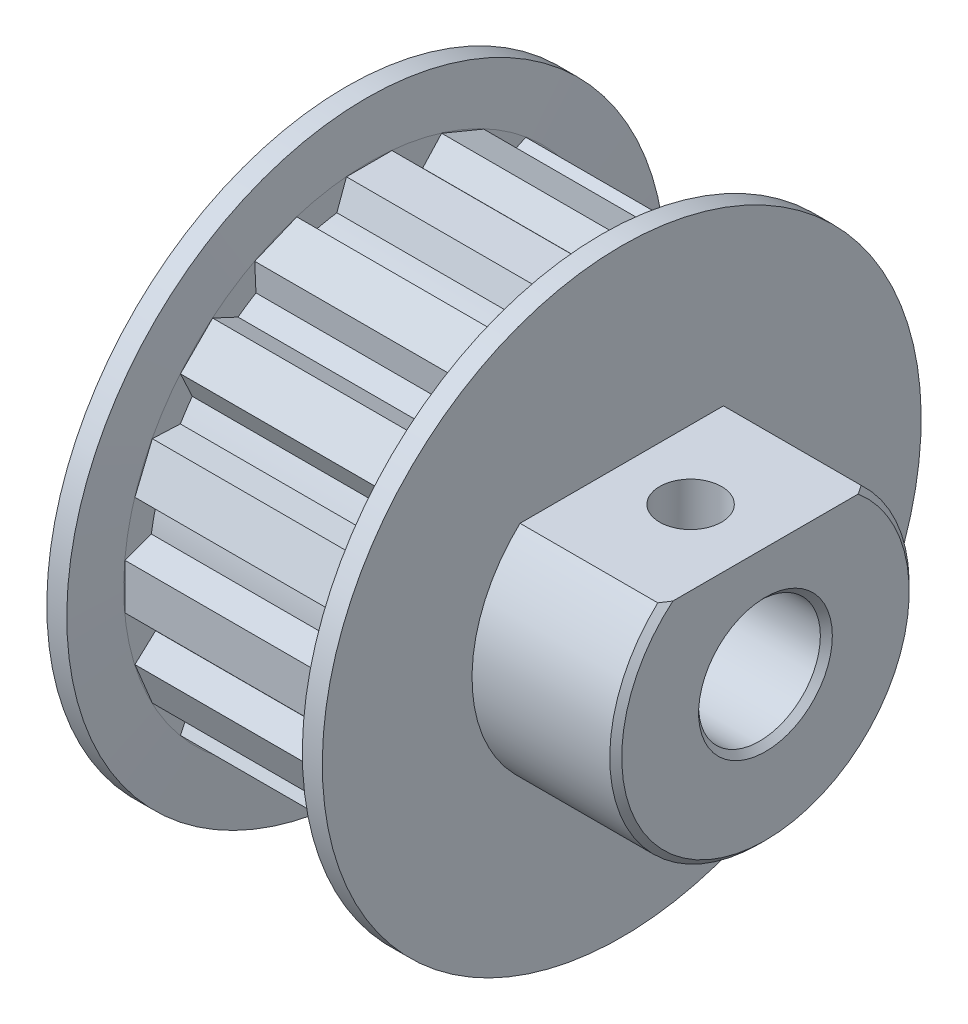
SolidWorks part; units mm, degrees
ref_plane "Front Plane" through (0, 0, 0) normal (0, 0, 1) x (1, 0, 0)
ref_plane "Top Plane" through (0, 0, 0) normal (0, 1, 0) x (1, 0, 0)
ref_plane "Right Plane" through (0, 0, 0) normal (1, 0, 0) x (0, 0, -1)
sketch "Sketch1" plane through (0, 0, 0) normal (0, 0, 1) x (1, 0, 0)
  line L0 (0, 15) -> (0, 0)
  line L1 (0, 0) -> (13.8, 0)
  line L2 (13.8, 0) -> (13.8, 15)
  line L3 (13.8, 15) -> (12.8, 15)
  line L4 (12.8, 15) -> (12.65, 12.3)
  line L5 (12.65, 12.3) -> (12.65, 11.0324)
  line L6 (12.65, 11.0324) -> (1.15, 11.0324)
  line L7 (1.15, 11.0324) -> (1.15, 12.3)
  line L8 (1.15, 12.3) -> (1, 15)
  line L9 (1, 15) -> (0, 15)
  line L10 (0, 0) -> (13.8, 0) construction
  dimension "D1" = 11.5
  dimension "D2" = 13.8
  dimension "D3" = 1.15
revolve "Revolve1" add sketch "Sketch1" angle 360 about L10
sketch "Sketch2" plane through (13.8, 0, 0) normal (1, 0, 0) x (0, 0, -1)
  circle A0 centre (0, 0) radius 7.5
extrude "Boss-Extrude1" add sketch "Sketch2" along normal blind 7.2
hole_wizard "Ø6.0 (6) Diameter Hole1" positions "Sketch4" profile "Sketch3" hole size "Ø6.0" standard "ANSI Metric"
sketch "Sketch4" plane through (21, 0, 0) normal (1, 0, 0) x (0, 0, -1)
  point P0 (0, 0)
sketch "Sketch3" plane through (21, 0, 0) normal (0, 1, 0) x (0, 0, -1)
  line L0 (0, 0) -> (0, 21)
  line L1 (0, 21) -> (3.05, 21)
  line L2 (3.05, 21) -> (3.05, 0)
  line L5 (3.05, 0) -> (0, 0)
  line L11 (0, -6.35) -> (0, 107.95) construction
  dimension "Thru Hole Dia." = 6.1
  dimension "Thru Hole Depth" = 21
ref_plane "Plane1" through (0, 0, 0) normal (0, -1, 0) x (1, 0, 0)
sketch "Sketch5" plane through (0, 0, 0) normal (0, -1, 0) x (1, 0, 0)
  line L0 (12.65, 12.2324) -> (1.15, 12.2324)
rib "Rib1" sketch "Sketch5" sketch "Sketch5" thickness 2.2803 extrusion direction parallel to sketch draft on yes draft angle 20 parameters "D1"=2.2803, "D3"=20
ref_plane "Plane2" through (0, 0, 0) normal (0, 0, -1) x (-1, 0, 0)
sketch "Sketch6" plane through (0, 0, 0) normal (0, 0, -1) x (-1, 0, 0)
  line L0 (-12.65, -12.2324) -> (-1.15, -12.2324)
rib "Rib2" sketch "Sketch6" sketch "Sketch6" thickness 2.2803 extrusion direction parallel to sketch draft on yes draft angle 20 parameters "D1"=2.2803, "D3"=20
sketch "Sketch7" plane through (0, 0, 0) normal (0, 1, 0) x (1, 0, 0)
  line L0 (12.65, 12.2324) -> (1.15, 12.2324)
rib "Rib3" sketch "Sketch7" sketch "Sketch7" thickness 2.2803 extrusion direction parallel to sketch draft on yes draft angle 20 parameters "D1"=2.2803, "D3"=20
sketch "Sketch8" plane through (0, 0, 0) normal (0, 0, 1) x (1, 0, 0)
  line L0 (12.65, 12.2324) -> (1.15, 12.2324)
rib "Rib4" sketch "Sketch8" sketch "Sketch8" thickness 2.2803 extrusion direction parallel to sketch draft on yes draft angle 20 parameters "D1"=2.2803, "D3"=20
ref_plane "Plane3" through (0, 0, 0) normal (0, -0.9239, -0.3827) x (1, 0, 0)
sketch "Sketch9" plane through (0, 0, 0) normal (0, -0.9239, -0.3827) x (1, 0, 0)
  line L0 (12.65, 12.2324) -> (1.15, 12.2324)
rib "Rib5" sketch "Sketch9" sketch "Sketch9" thickness 2.2803 extrusion direction parallel to sketch draft on yes draft angle 20 parameters "D1"=2.2803, "D3"=20
ref_plane "Plane4" through (0, 0, 0) normal (0, 0.9239, -0.3827) x (-1, 0, 0)
sketch "Sketch10" plane through (0, 0, 0) normal (0, 0.9239, -0.3827) x (-1, 0, 0)
  line L0 (-12.65, -12.2324) -> (-1.15, -12.2324)
rib "Rib6" sketch "Sketch10" sketch "Sketch10" thickness 2.2803 extrusion direction parallel to sketch draft on yes draft angle 20 parameters "D1"=2.2803, "D3"=20
ref_plane "Plane5" through (0, 0, 0) normal (0, -0.3827, -0.9239) x (1, 0, 0)
sketch "Sketch11" plane through (0, 0, 0) normal (0, -0.3827, -0.9239) x (1, 0, 0)
  line L0 (12.65, 12.2324) -> (1.15, 12.2324)
rib "Rib7" sketch "Sketch11" sketch "Sketch11" thickness 2.2803 extrusion direction parallel to sketch draft on yes draft angle 20 parameters "D1"=2.2803, "D3"=20
ref_plane "Plane6" through (0, 0, 0) normal (0, 0.7071, -0.7071) x (-1, 0, 0)
sketch "Sketch12" plane through (0, 0, 0) normal (0, 0.7071, -0.7071) x (-1, 0, 0)
  line L0 (-12.65, -12.2324) -> (-1.15, -12.2324)
rib "Rib8" sketch "Sketch12" sketch "Sketch12" thickness 2.2803 extrusion direction parallel to sketch draft on yes draft angle 20 parameters "D1"=2.2803, "D3"=20
ref_plane "Plane7" through (0, 0, 0) normal (0, -0.7071, 0.7071) x (1, 0, 0)
sketch "Sketch13" plane through (0, 0, 0) normal (0, -0.7071, 0.7071) x (1, 0, 0)
  line L0 (12.65, 12.2324) -> (1.15, 12.2324)
rib "Rib9" sketch "Sketch13" sketch "Sketch13" thickness 2.2803 extrusion direction parallel to sketch draft on yes draft angle 20 parameters "D1"=2.2803, "D3"=20
ref_plane "Plane8" through (0, 0, 0) normal (0, 0.3827, -0.9239) x (-1, 0, 0)
sketch "Sketch14" plane through (0, 0, 0) normal (0, 0.3827, -0.9239) x (-1, 0, 0)
  line L0 (-12.65, -12.2324) -> (-1.15, -12.2324)
rib "Rib10" sketch "Sketch14" sketch "Sketch14" thickness 2.2803 extrusion direction parallel to sketch draft on yes draft angle 20 parameters "D1"=2.2803, "D3"=20
ref_plane "Plane9" through (0, 0, 0) normal (0, -0.7071, -0.7071) x (1, 0, 0)
sketch "Sketch15" plane through (0, 0, 0) normal (0, -0.7071, -0.7071) x (1, 0, 0)
  line L0 (12.65, 12.2324) -> (1.15, 12.2324)
rib "Rib11" sketch "Sketch15" sketch "Sketch15" thickness 2.2803 extrusion direction parallel to sketch draft on yes draft angle 20 parameters "D1"=2.2803, "D3"=20
ref_plane "Plane10" through (0, 0, 0) normal (0, 0.7071, 0.7071) x (-1, 0, 0)
sketch "Sketch16" plane through (0, 0, 0) normal (0, 0.7071, 0.7071) x (-1, 0, 0)
  line L0 (-12.65, -12.2324) -> (-1.15, -12.2324)
rib "Rib12" sketch "Sketch16" sketch "Sketch16" thickness 2.2803 extrusion direction parallel to sketch draft on yes draft angle 20 parameters "D1"=2.2803, "D3"=20
ref_plane "Plane11" through (0, 0, 0) normal (0, 0.9239, 0.3827) x (-1, 0, 0)
sketch "Sketch17" plane through (0, 0, 0) normal (0, 0.9239, 0.3827) x (-1, 0, 0)
  line L0 (-12.65, -12.2324) -> (-1.15, -12.2324)
rib "Rib13" sketch "Sketch17" sketch "Sketch17" thickness 2.2803 extrusion direction parallel to sketch draft on yes draft angle 20 parameters "D1"=2.2803, "D3"=20
ref_plane "Plane12" through (0, 0, 0) normal (0, -0.3827, 0.9239) x (1, 0, 0)
sketch "Sketch18" plane through (0, 0, 0) normal (0, -0.3827, 0.9239) x (1, 0, 0)
  line L0 (12.65, 12.2324) -> (1.15, 12.2324)
rib "Rib14" sketch "Sketch18" sketch "Sketch18" thickness 2.2803 extrusion direction parallel to sketch draft on yes draft angle 20 parameters "D1"=2.2803, "D3"=20
ref_plane "Plane13" through (0, 0, 0) normal (0, 0.3827, 0.9239) x (-1, 0, 0)
sketch "Sketch19" plane through (0, 0, 0) normal (0, 0.3827, 0.9239) x (-1, 0, 0)
  line L0 (-12.65, -12.2324) -> (-1.15, -12.2324)
rib "Rib15" sketch "Sketch19" sketch "Sketch19" thickness 2.2803 extrusion direction parallel to sketch draft on yes draft angle 20 parameters "D1"=2.2803, "D3"=20
ref_plane "Plane14" through (0, 0, 0) normal (0, -0.9239, 0.3827) x (1, 0, 0)
sketch "Sketch20" plane through (0, 0, 0) normal (0, -0.9239, 0.3827) x (1, 0, 0)
  line L0 (12.65, 12.2324) -> (1.15, 12.2324)
rib "Rib16" sketch "Sketch20" sketch "Sketch20" thickness 2.2803 extrusion direction parallel to sketch draft on yes draft angle 20 parameters "D1"=2.2803, "D3"=20
chamfer "Chamfer1" distance 0.3 angle 45 3 edges at (21, 0, -7.5) (0, 0, -3.05) (21, 0, -3.05)
sketch "Sketch21" plane through (21, 0, 0) normal (1, 0, 0) x (0, 0, -1)
  line L0 (-5.095, 5.5037) -> (5.095, 5.5037)
  line L1 (-5.095, 5.5037) -> (-5.095, 7.871)
  line L2 (5.095, 5.5037) -> (5.095, 7.871)
  line L3 (-5.095, 7.871) -> (5.095, 7.871)
  circle A0 centre (0, 0) radius 7.5 construction
  point P6 (-5.4189, 5.1851)
  point P7 (0, 0)
extrude "Cut-Extrude1" cut sketch "Sketch21" against normal blind 7.2
sketch "Sketch22" plane through (0, 5.5037, 0) normal (0, 1, 0) x (1, 0, 0)
  line L0 (21, 0) -> (13.8, 0) construction
  line L1 (21, -4.6421) -> (21, 4.6421) construction
  line L2 (13.8, -15) -> (13.8, 15) construction
  line L3 (17.25, 5.095) -> (17.25, -5.095) construction
  line L4 (13.8, 5.095) -> (20.7, 5.095) construction
  line L5 (13.8, -5.095) -> (20.7, -5.095) construction
  circle A0 centre (17.25, 0) radius 1.55
  dimension "D1" = 3.1
extrude "Cut-Extrude2" cut sketch "Sketch22" against normal blind 5.2
